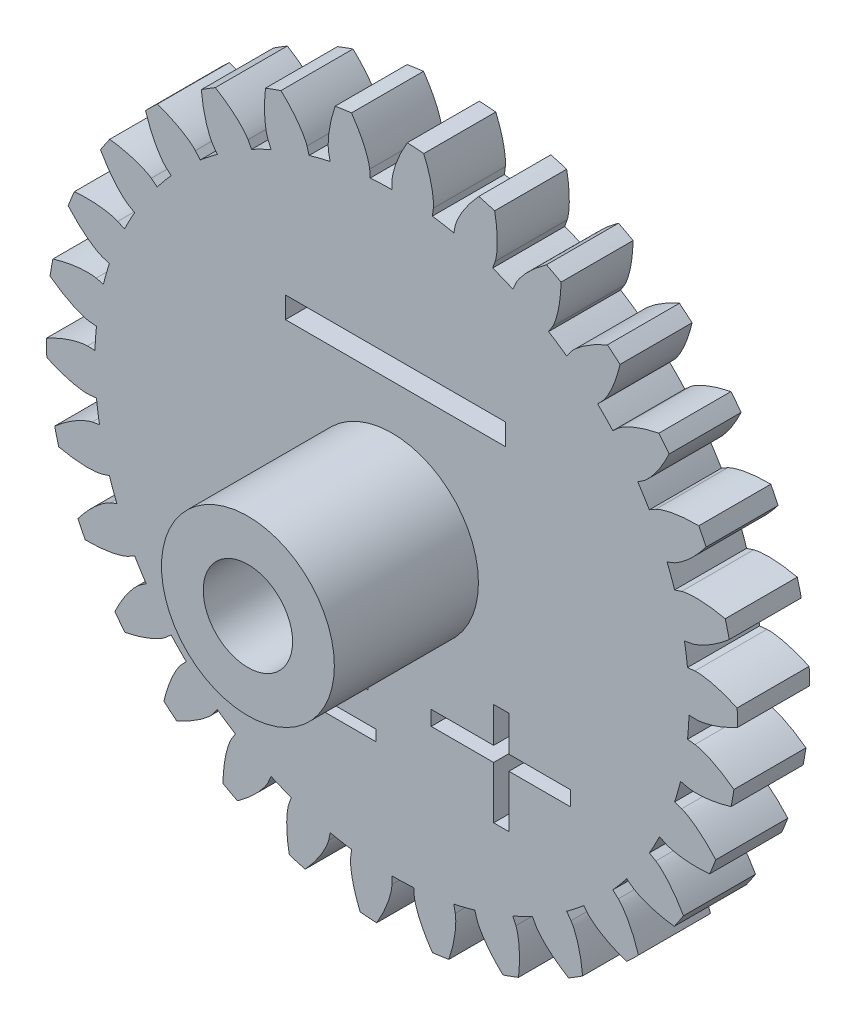
SolidWorks part; units mm, degrees
ref_plane "前视基准面" through (0, 0, 0) normal (0, 0, 1) x (1, 0, 0)
ref_plane "上视基准面" through (0, 0, 0) normal (0, 1, 0) x (1, 0, 0)
ref_plane "右视基准面" through (0, 0, 0) normal (1, 0, 0) x (0, 0, -1)
sketch "草图1" plane through (0, 0, 0) normal (0, 0, 1) x (1, 0, 0)
  line L0 (0, 0) -> (0.3541, 22.4972) construction
  line L1 (0, 0) -> (2.0291, 29.7506) construction
  line L2 (0, 0) -> (5.2133, 29.8652) construction
  circle A0 centre (0, 0) radius 22.5
  circle A1 centre (0, 0) radius 24
  circle A2 centre (0, 0) radius 20.625
  spline S0 degree 4 poles (0, 21.1431) (0.0004, 21.1602) (0.0026, 21.2083) (0.0115, 21.2988) (0.0325, 21.446) (0.069, 21.6322) (0.127, 21.8709) (0.2093, 22.149) (0.3142, 22.451) (0.4437, 22.7748) (0.5865, 23.0933) (0.7411, 23.4062) (0.9065, 23.7136) (1.1191, 24.0799) (1.3926, 24.5114) (1.7356, 25.0015) (2.1566, 25.5426) (2.6112, 26.0723) (3.0895, 26.5812) (3.5886, 27.069) (4.1076, 27.5366) (4.6431, 27.9833) (5.1275, 28.3576) (5.5491, 28.6644) (5.9109, 28.9144) (6.1952, 29.1048) (6.5001, 29.3003) (6.7749, 29.4718) (7.175, 29.7103) (7.4719, 29.8798) (7.9311, 30.1336) (8.0994, 30.2164) (8.2684, 30.3055) knots 0 0 0 0 0 0.005377 0.015084 0.028532 0.04661 0.064855 0.092111 0.119476 0.146842 0.174209 0.201575 0.228941 0.256307 0.307035 0.361767 0.4165 0.471232 0.525964 0.580697 0.635429 0.690161 0.744894 0.77226 0.799626 0.826992 0.854358 0.881725 0.909091 0.954545 1 1 1 1 1 construction
  spline S1 degree 4 poles (0, 21.1431) (0.0004, 21.1602) (0.0026, 21.2083) (0.0115, 21.2988) (0.0325, 21.446) (0.069, 21.6322) (0.127, 21.8709) (0.2093, 22.149) (0.3142, 22.451) (0.4437, 22.7748) (0.5865, 23.0933) (0.7411, 23.4062) (0.8806, 23.6655) (0.9833, 23.8453) (1.0443, 23.9485) (1.0609, 23.9765) knots 0 0 0 0 0 0.005377 0.015084 0.028532 0.04661 0.064855 0.092111 0.119476 0.146842 0.174209 0.201575 0.228941 0.239168 0.239168 0.239168 0.239168 0.239168
  spline S2 degree 2 poles (0, 21.1431) (0, 20.884) (0, 20.625) knots 0 0 0 1 1 1
  spline S3 degree 2 poles (2.8708, 20.9473) (2.8356, 20.6906) (2.8004, 20.434) knots 0 0 0 1 1 1
  spline S4 degree 4 poles (2.8708, 20.9473) (2.8727, 20.9643) (2.877, 21.0122) (2.8805, 21.1032) (2.8796, 21.2518) (2.8688, 21.4412) (2.8438, 21.6856) (2.8, 21.9723) (2.737, 22.2857) (2.6527, 22.6241) (2.5545, 22.9591) (2.4438, 23.2901) (2.3408, 23.5659) (2.2634, 23.758) (2.2171, 23.8685) (2.2044, 23.8986) knots 0 0 0 0 0 0.005377 0.015084 0.028532 0.04661 0.064855 0.092111 0.119476 0.146842 0.174209 0.201575 0.228941 0.239168 0.239168 0.239168 0.239168 0.239168
  spline S5 degree 2 poles (4.3959, 20.6811) (4.342, 20.4277) (4.2882, 20.1743) knots 0 0 0 1 1 1
  spline S6 degree 4 poles (4.3959, 20.6811) (4.3998, 20.6977) (4.412, 20.7443) (4.4395, 20.831) (4.4907, 20.9706) (4.565, 21.1451) (4.6714, 21.3665) (4.8097, 21.6215) (4.9752, 21.895) (5.1692, 22.1848) (5.3751, 22.4667) (5.5914, 22.7406) (5.7817, 22.9653) (5.9196, 23.1198) (6.0006, 23.2081) (6.0228, 23.232) knots 0 0 0 0 0 0.005377 0.015084 0.028532 0.04661 0.064855 0.092111 0.119476 0.146842 0.174209 0.201575 0.228941 0.239168 0.239168 0.239168 0.239168 0.239168
  dimension "D1" = 45
  dimension "D2" = 48
  dimension "D3" = 41.25
  dimension "D4" = 3
  dimension "D5" = 9
sketch "草图2" plane through (0, 0, 0) normal (0, 0, 1) x (1, 0, 0)
  circle A0 centre (0, 0) radius 24 construction
  circle A1 centre (0, 0) radius 20.625 construction
  arc A2 (2.2044, 23.8986) -> (1.0609, 23.9765) centre (0, 0) ccw
  arc A3 (4.2882, 20.1743) -> (2.8004, 20.434) centre (0, 0) ccw
  arc A4 (7.125, 22.918) -> (6.0228, 23.232) centre (0, 0) ccw
  arc A5 (8.3889, 18.8419) -> (6.9877, 19.4052) centre (0, 0) ccw
  arc A6 (11.7342, 20.9358) -> (10.7214, 21.4721) centre (0, 0) ccw
  arc A7 (12.1231, 16.686) -> (10.8696, 17.5284) centre (0, 0) ccw
  arc A8 (15.8306, 18.0386) -> (14.9514, 18.7738) centre (0, 0) ccw
  arc A9 (15.3274, 13.8008) -> (14.2764, 14.8854) centre (0, 0) ccw
  arc A10 (19.2351, 14.3531) -> (18.528, 15.255) centre (0, 0) ccw
  arc A11 (17.8618, 10.3125) -> (17.0593, 11.5919) centre (0, 0) ccw
  arc A12 (21.7989, 10.0402) -> (21.2948, 11.0695) centre (0, 0) ccw
  arc A13 (19.6155, 6.3735) -> (19.0966, 7.7918) centre (0, 0) ccw
  arc A14 (23.4101, 5.2886) -> (23.1309, 6.4001) centre (0, 0) ccw
  arc A15 (20.512, 2.1559) -> (20.2993, 3.6511) centre (0, 0) ccw
  arc A16 (23.9981, 0.3058) -> (23.9561, 1.4511) centre (0, 0) ccw
  arc A17 (20.512, -2.1559) -> (20.6148, -0.6491) centre (0, 0) ccw
  arc A18 (23.5372, -4.6904) -> (23.7343, -3.5614) centre (0, 0) ccw
  arc A19 (19.6155, -6.3735) -> (20.0293, -4.921) centre (0, 0) ccw
  arc A20 (22.0477, -9.4815) -> (22.4752, -8.4182) centre (0, 0) ccw
  arc A21 (17.8618, -10.3125) -> (18.5685, -8.9778) centre (0, 0) ccw
  arc A22 (19.5946, -13.8583) -> (20.2338, -12.9071) centre (0, 0) ccw
  arc A23 (15.3274, -13.8008) -> (16.2962, -12.6422) centre (0, 0) ccw
  arc A24 (16.2851, -17.6294) -> (17.1081, -16.8319) centre (0, 0) ccw
  arc A25 (12.1231, -16.686) -> (13.3116, -15.7541) centre (0, 0) ccw
  arc A26 (12.2639, -20.63) -> (13.2347, -20.021) centre (0, 0) ccw
  arc A27 (8.3889, -18.8419) -> (9.7452, -18.1775) centre (0, 0) ccw
  arc A28 (7.7066, -22.729) -> (8.7829, -22.3352) centre (0, 0) ccw
  arc A29 (4.2882, -20.1743) -> (5.753, -19.8064) centre (0, 0) ccw
  arc A30 (2.8126, -23.8346) -> (3.9472, -23.6732) centre (0, 0) ccw
  arc A31 (0, -20.625) -> (1.5092, -20.5697) centre (0, 0) ccw
  arc A32 (-2.2044, -23.8986) -> (-1.0609, -23.9765) centre (0, 0) ccw
  arc A33 (-4.2882, -20.1743) -> (-2.8004, -20.434) centre (0, 0) ccw
  arc A34 (-7.125, -22.918) -> (-6.0228, -23.232) centre (0, 0) ccw
  arc A35 (-8.3889, -18.8419) -> (-6.9877, -19.4052) centre (0, 0) ccw
  arc A36 (-11.7342, -20.9358) -> (-10.7214, -21.4721) centre (0, 0) ccw
  arc A37 (-12.1231, -16.686) -> (-10.8696, -17.5284) centre (0, 0) ccw
  arc A38 (-15.8306, -18.0386) -> (-14.9514, -18.7738) centre (0, 0) ccw
  arc A39 (-15.3274, -13.8008) -> (-14.2764, -14.8854) centre (0, 0) ccw
  arc A40 (-19.2351, -14.3531) -> (-18.528, -15.255) centre (0, 0) ccw
  arc A41 (-17.8618, -10.3125) -> (-17.0593, -11.5919) centre (0, 0) ccw
  arc A42 (-21.7989, -10.0402) -> (-21.2948, -11.0695) centre (0, 0) ccw
  arc A43 (-19.6155, -6.3735) -> (-19.0966, -7.7918) centre (0, 0) ccw
  arc A44 (-23.4101, -5.2886) -> (-23.1309, -6.4001) centre (0, 0) ccw
  arc A45 (-20.512, -2.1559) -> (-20.2993, -3.6511) centre (0, 0) ccw
  arc A46 (-23.9981, -0.3058) -> (-23.9561, -1.4511) centre (0, 0) ccw
  arc A47 (-20.512, 2.1559) -> (-20.6148, 0.6491) centre (0, 0) ccw
  arc A48 (-23.5372, 4.6904) -> (-23.7343, 3.5614) centre (0, 0) ccw
  arc A49 (-19.6155, 6.3735) -> (-20.0293, 4.921) centre (0, 0) ccw
  arc A50 (-22.0477, 9.4815) -> (-22.4752, 8.4182) centre (0, 0) ccw
  arc A51 (-17.8618, 10.3125) -> (-18.5685, 8.9778) centre (0, 0) ccw
  arc A52 (-19.5946, 13.8583) -> (-20.2338, 12.9071) centre (0, 0) ccw
  arc A53 (-15.3274, 13.8008) -> (-16.2962, 12.6422) centre (0, 0) ccw
  arc A54 (-16.2851, 17.6294) -> (-17.1081, 16.8319) centre (0, 0) ccw
  arc A55 (-12.1231, 16.686) -> (-13.3116, 15.7541) centre (0, 0) ccw
  arc A56 (-12.2639, 20.63) -> (-13.2347, 20.021) centre (0, 0) ccw
  arc A57 (-8.3889, 18.8419) -> (-9.7452, 18.1775) centre (0, 0) ccw
  arc A58 (-7.7066, 22.729) -> (-8.7829, 22.3352) centre (0, 0) ccw
  arc A59 (-4.2882, 20.1743) -> (-5.753, 19.8064) centre (0, 0) ccw
  arc A60 (-2.8126, 23.8346) -> (-3.9472, 23.6732) centre (0, 0) ccw
  arc A61 (0, 20.625) -> (-1.5092, 20.5697) centre (0, 0) ccw
  spline S2 degree 2 poles (274.4242, 2002.4129) (2.8348, 20.6849) (-268.7546, -1961.043) knots -3860.352679 -3860.352679 -3860.352679 3861.374869 3861.374869 3861.374869 only from (2.8708, 20.9473) to (2.8004, 20.434) construction
  spline S3 degree 4 poles (-1979.2072, 287.1741) (-31.6416, 21.293) (1.8963, 18.3394) (2.8884, 19.7632) (2.8796, 21.2518) (2.8688, 21.4412) (2.8438, 21.6856) (2.8, 21.9723) (2.737, 22.2857) (2.6527, 22.6241) (2.5545, 22.9591) (2.4438, 23.2901) (-2.8505, 37.472) (-34.1394, 41.319) (58.2669, 25.3379) (-1676.5067, -1063.1461) knots -0.420205 -0.420205 -0.420205 -0.420205 -0.420205 0.005377 0.015084 0.028532 0.04661 0.064855 0.092111 0.119476 0.146842 0.174209 0.201575 0.228941 4.89418 4.89418 4.89418 4.89418 4.89418 only from (2.8708, 20.9473) to (2.2044, 23.8986) construction
  spline S4 degree 2 poles (0, 2021.1299) (0, 20.8783) (0, -1979.3733) knots -3860.352679 -3860.352679 -3860.352679 3861.374869 3861.374869 3861.374869 only from (0, 21.1431) to (0, 20.625) construction
  spline S5 degree 4 poles (1999.8702, 15.7826) (34.2397, 16.7996) (0.6114, 18.4271) (-0.1783, 19.9724) (0.0325, 21.446) (0.069, 21.6322) (0.127, 21.8709) (0.2093, 22.149) (0.3142, 22.451) (0.4437, 22.7748) (0.5865, 23.0933) (0.7411, 23.4062) (7.912, 36.7379) (39.4334, 36.301) (-54.287, 33.0146) (1516.6297, -1280.9329) knots -0.420205 -0.420205 -0.420205 -0.420205 -0.420205 0.005377 0.015084 0.028532 0.04661 0.064855 0.092111 0.119476 0.146842 0.174209 0.201575 0.228941 4.89418 4.89418 4.89418 4.89418 4.89418 only from (0, 21.1431) to (1.0609, 23.9765) construction
  spline S6 degree 4 poles (4.3959, 20.6811) (4.3998, 20.6977) (4.412, 20.7443) (4.4395, 20.831) (4.4907, 20.9706) (4.565, 21.1451) (4.6714, 21.3665) (4.8097, 21.6215) (4.9752, 21.895) (5.1692, 22.1848) (5.3751, 22.4667) (5.5914, 22.7406) (5.7817, 22.9653) (5.9196, 23.1198) (6.0006, 23.2081) (6.0228, 23.232) knots 0 0 0 0 0 0.005377 0.015084 0.028532 0.04661 0.064855 0.092111 0.119476 0.146842 0.174209 0.201575 0.228941 0.239168 0.239168 0.239168 0.239168 0.239168
  spline S7 degree 2 poles (4.3959, 20.6811) (4.342, 20.4277) (4.2882, 20.1743) knots 0 0 0 1 1 1
  spline S8 degree 2 poles (2.8708, 20.9473) (2.8356, 20.6906) (2.8004, 20.434) knots 0 0 0 1 1 1
  spline S9 degree 4 poles (2.8708, 20.9473) (2.8727, 20.9643) (2.877, 21.0122) (2.8805, 21.1032) (2.8796, 21.2518) (2.8688, 21.4412) (2.8438, 21.6856) (2.8, 21.9723) (2.737, 22.2857) (2.6527, 22.6241) (2.5545, 22.9591) (2.4438, 23.2901) (2.3408, 23.5659) (2.2634, 23.758) (2.2171, 23.8685) (2.2044, 23.8986) knots 0 0 0 0 0 0.005377 0.015084 0.028532 0.04661 0.064855 0.092111 0.119476 0.146842 0.174209 0.201575 0.228941 0.239168 0.239168 0.239168 0.239168 0.239168
  spline S10 degree 2 poles (0, 21.1431) (0, 20.884) (0, 20.625) knots 0 0 0 1 1 1
  spline S11 degree 4 poles (0, 21.1431) (0.0004, 21.1602) (0.0026, 21.2083) (0.0115, 21.2988) (0.0325, 21.446) (0.069, 21.6322) (0.127, 21.8709) (0.2093, 22.149) (0.3142, 22.451) (0.4437, 22.7748) (0.5865, 23.0933) (0.7411, 23.4062) (0.8806, 23.6655) (0.9833, 23.8453) (1.0443, 23.9485) (1.0609, 23.9765) knots 0 0 0 0 0 0.005377 0.015084 0.028532 0.04661 0.064855 0.092111 0.119476 0.146842 0.174209 0.201575 0.228941 0.239168 0.239168 0.239168 0.239168 0.239168
  spline S12 degree 4 poles (7.1632, 19.8927) (7.1687, 19.9089) (7.1828, 19.9549) (7.2052, 20.0431) (7.2352, 20.1887) (7.264, 20.3762) (7.2903, 20.6204) (7.3071, 20.91) (7.3107, 21.2297) (7.2985, 21.5782) (7.2721, 21.9262) (7.2326, 22.2731) (7.1893, 22.5642) (7.1535, 22.7682) (7.1312, 22.886) (7.125, 22.918) knots 0 0 0 0 0 0.005377 0.015084 0.028532 0.04661 0.064855 0.092111 0.119476 0.146842 0.174209 0.201575 0.228941 0.239168 0.239168 0.239168 0.239168 0.239168
  spline S13 degree 2 poles (7.1632, 19.8927) (7.0754, 19.649) (6.9877, 19.4052) knots 0 0 0 1 1 1
  spline S14 degree 4 poles (8.5997, 19.3152) (8.607, 19.3307) (8.6286, 19.3736) (8.6735, 19.4528) (8.7526, 19.5786) (8.8616, 19.7339) (9.0117, 19.9284) (9.2, 20.149) (9.4187, 20.3822) (9.6687, 20.6253) (9.9287, 20.8582) (10.1972, 21.0812) (10.4301, 21.2613) (10.5971, 21.3838) (10.6947, 21.4533) (10.7214, 21.4721) knots 0 0 0 0 0 0.005377 0.015084 0.028532 0.04661 0.064855 0.092111 0.119476 0.146842 0.174209 0.201575 0.228941 0.239168 0.239168 0.239168 0.239168 0.239168
  spline S15 degree 2 poles (8.5997, 19.3152) (8.4943, 19.0785) (8.3889, 18.8419) knots 0 0 0 1 1 1
  spline S16 degree 4 poles (11.1426, 17.9687) (11.1513, 17.9834) (11.1747, 18.0254) (11.2149, 18.1071) (11.2746, 18.2432) (11.3417, 18.4207) (11.4182, 18.6541) (11.4949, 18.9338) (11.5648, 19.2458) (11.6254, 19.5892) (11.6719, 19.9352) (11.7054, 20.2826) (11.7235, 20.5764) (11.731, 20.7834) (11.7336, 20.9032) (11.7342, 20.9358) knots 0 0 0 0 0 0.005377 0.015084 0.028532 0.04661 0.064855 0.092111 0.119476 0.146842 0.174209 0.201575 0.228941 0.239168 0.239168 0.239168 0.239168 0.239168
  spline S17 degree 2 poles (11.1426, 17.9687) (11.0061, 17.7485) (10.8696, 17.5284) knots 0 0 0 1 1 1
  spline S18 degree 4 poles (12.4276, 17.1051) (12.438, 17.1188) (12.468, 17.1563) (12.5284, 17.2244) (12.632, 17.331) (12.7709, 17.4603) (12.9581, 17.6193) (13.1882, 17.7959) (13.4505, 17.9785) (13.7456, 18.1644) (14.0484, 18.3381) (14.3574, 18.5004) (14.6226, 18.6282) (14.8115, 18.7133) (14.9214, 18.761) (14.9514, 18.7738) knots 0 0 0 0 0 0.005377 0.015084 0.028532 0.04661 0.064855 0.092111 0.119476 0.146842 0.174209 0.201575 0.228941 0.239168 0.239168 0.239168 0.239168 0.239168
  spline S19 degree 2 poles (12.4276, 17.1051) (12.2753, 16.8955) (12.1231, 16.686) knots 0 0 0 1 1 1
  spline S20 degree 4 poles (14.635, 15.2593) (14.6466, 15.272) (14.6782, 15.3082) (14.7345, 15.3797) (14.8212, 15.5005) (14.9238, 15.66) (15.0471, 15.8725) (15.1803, 16.1302) (15.3135, 16.4207) (15.4442, 16.7441) (15.5616, 17.0728) (15.6666, 17.4057) (15.7454, 17.6893) (15.7958, 17.8902) (15.8232, 18.0069) (15.8306, 18.0386) knots 0 0 0 0 0 0.005377 0.015084 0.028532 0.04661 0.064855 0.092111 0.119476 0.146842 0.174209 0.201575 0.228941 0.239168 0.239168 0.239168 0.239168 0.239168
  spline S21 degree 2 poles (14.635, 15.2593) (14.4557, 15.0724) (14.2764, 14.8854) knots 0 0 0 1 1 1
  spline S22 degree 4 poles (15.7124, 14.1475) (15.7254, 14.1587) (15.7626, 14.1891) (15.8358, 14.2432) (15.9592, 14.326) (16.122, 14.4235) (16.3382, 14.5401) (16.5999, 14.6651) (16.8946, 14.7891) (17.2219, 14.9095) (17.5541, 15.0165) (17.8901, 15.111) (18.1761, 15.1809) (18.3785, 15.2249) (18.496, 15.2487) (18.528, 15.255) knots 0 0 0 0 0 0.005377 0.015084 0.028532 0.04661 0.064855 0.092111 0.119476 0.146842 0.174209 0.201575 0.228941 0.239168 0.239168 0.239168 0.239168 0.239168
  spline S23 degree 2 poles (15.7124, 14.1475) (15.5199, 13.9742) (15.3274, 13.8008) knots 0 0 0 1 1 1
  spline S24 degree 4 poles (17.4878, 11.8831) (17.5017, 11.893) (17.5402, 11.9219) (17.6102, 11.9801) (17.72, 12.0802) (17.8536, 12.215) (18.0184, 12.3971) (18.2022, 12.6215) (18.3929, 12.878) (18.588, 13.1671) (18.7712, 13.4643) (18.9431, 13.768) (19.0792, 14.0291) (19.1702, 14.2152) (19.2213, 14.3236) (19.2351, 14.3531) knots 0 0 0 0 0 0.005377 0.015084 0.028532 0.04661 0.064855 0.092111 0.119476 0.146842 0.174209 0.201575 0.228941 0.239168 0.239168 0.239168 0.239168 0.239168
  spline S25 degree 2 poles (17.4878, 11.8831) (17.2735, 11.7375) (17.0593, 11.5919) knots 0 0 0 1 1 1
  spline S26 degree 4 poles (18.3104, 10.5715) (18.3255, 10.5798) (18.3682, 10.6019) (18.4511, 10.6395) (18.589, 10.6948) (18.7685, 10.7564) (19.0042, 10.8255) (19.2862, 10.8933) (19.6002, 10.9534) (19.9454, 11.0031) (20.2926, 11.0387) (20.641, 11.0613) (20.9352, 11.0701) (21.1423, 11.0711) (21.2622, 11.0699) (21.2948, 11.0695) knots 0 0 0 0 0 0.005377 0.015084 0.028532 0.04661 0.064855 0.092111 0.119476 0.146842 0.174209 0.201575 0.228941 0.239168 0.239168 0.239168 0.239168 0.239168
  spline S27 degree 2 poles (18.3104, 10.5715) (18.0861, 10.442) (17.8618, 10.3125) knots 0 0 0 1 1 1
  spline S28 degree 4 poles (19.5763, 7.9875) (19.592, 7.9943) (19.6356, 8.0145) (19.7161, 8.057) (19.8444, 8.1321) (20.0031, 8.2361) (20.2021, 8.38) (20.4286, 8.5613) (20.6685, 8.7725) (20.9194, 9.0148) (21.1604, 9.2673) (21.3917, 9.5287) (21.5791, 9.7558) (21.7068, 9.9188) (21.7793, 10.0142) (21.7989, 10.0402) knots 0 0 0 0 0 0.005377 0.015084 0.028532 0.04661 0.064855 0.092111 0.119476 0.146842 0.174209 0.201575 0.228941 0.239168 0.239168 0.239168 0.239168 0.239168
  spline S29 degree 2 poles (19.5763, 7.9875) (19.3364, 7.8896) (19.0966, 7.7918) knots 0 0 0 1 1 1
  spline S30 degree 4 poles (20.1083, 6.5336) (20.1247, 6.5385) (20.1711, 6.5512) (20.26, 6.5708) (20.4064, 6.5962) (20.5947, 6.6191) (20.8397, 6.6377) (21.1296, 6.6454) (21.4492, 6.6389) (21.7972, 6.6158) (22.1443, 6.5784) (22.4897, 6.5281) (22.7793, 6.4755) (22.9821, 6.4334) (23.0991, 6.4073) (23.1309, 6.4001) knots 0 0 0 0 0 0.005377 0.015084 0.028532 0.04661 0.064855 0.092111 0.119476 0.146842 0.174209 0.201575 0.228941 0.239168 0.239168 0.239168 0.239168 0.239168
  spline S31 degree 2 poles (20.1083, 6.5336) (19.8619, 6.4535) (19.6155, 6.3735) knots 0 0 0 1 1 1
  spline S32 degree 4 poles (20.8092, 3.7428) (20.826, 3.7462) (20.8728, 3.7569) (20.9604, 3.7817) (21.1015, 3.8285) (21.2783, 3.8973) (21.503, 3.9966) (21.7622, 4.1268) (22.0408, 4.2836) (22.3365, 4.4684) (22.6247, 4.6653) (22.9054, 4.8729) (23.1359, 5.056) (23.2947, 5.189) (23.3854, 5.2672) (23.4101, 5.2886) knots 0 0 0 0 0 0.005377 0.015084 0.028532 0.04661 0.064855 0.092111 0.119476 0.146842 0.174209 0.201575 0.228941 0.239168 0.239168 0.239168 0.239168 0.239168
  spline S33 degree 2 poles (20.8092, 3.7428) (20.5542, 3.697) (20.2993, 3.6511) knots 0 0 0 1 1 1
  spline S34 degree 4 poles (21.0273, 2.2101) (21.0443, 2.2115) (21.0924, 2.2143) (21.1834, 2.2149) (21.3319, 2.2093) (21.5209, 2.1926) (21.7643, 2.1598) (22.0495, 2.1071) (22.3608, 2.0343) (22.6964, 1.9393) (23.0281, 1.8306) (23.3555, 1.7095) (23.6279, 1.5979) (23.8175, 1.5146) (23.9265, 1.4648) (23.9561, 1.4511) knots 0 0 0 0 0 0.005377 0.015084 0.028532 0.04661 0.064855 0.092111 0.119476 0.146842 0.174209 0.201575 0.228941 0.239168 0.239168 0.239168 0.239168 0.239168
  spline S35 degree 2 poles (21.0273, 2.2101) (20.7696, 2.183) (20.512, 2.1559) knots 0 0 0 1 1 1
  spline S36 degree 4 poles (21.1326, -0.6654) (21.1498, -0.6656) (21.1978, -0.6649) (21.2887, -0.6589) (21.4364, -0.6424) (21.6236, -0.6119) (21.864, -0.5614) (22.1446, -0.4879) (22.4497, -0.3926) (22.7774, -0.2733) (23.1003, -0.1406) (23.418, 0.0041) (23.6815, 0.1353) (23.8645, 0.2324) (23.9695, 0.29) (23.9981, 0.3058) knots 0 0 0 0 0 0.005377 0.015084 0.028532 0.04661 0.064855 0.092111 0.119476 0.146842 0.174209 0.201575 0.228941 0.239168 0.239168 0.239168 0.239168 0.239168
  spline S37 degree 2 poles (21.1326, -0.6654) (20.8737, -0.6573) (20.6148, -0.6491) knots 0 0 0 1 1 1
  spline S38 degree 4 poles (21.0273, -2.2101) (21.0443, -2.2122) (21.0918, -2.2195) (21.181, -2.2378) (21.3251, -2.2741) (21.5065, -2.3298) (21.7378, -2.4124) (22.0058, -2.5233) (22.2951, -2.6593) (22.6036, -2.8219) (22.9055, -2.9972) (23.2005, -3.1837) (23.4438, -3.3495) (23.6119, -3.4705) (23.7082, -3.5418) (23.7343, -3.5614) knots 0 0 0 0 0 0.005377 0.015084 0.028532 0.04661 0.064855 0.092111 0.119476 0.146842 0.174209 0.201575 0.228941 0.239168 0.239168 0.239168 0.239168 0.239168
  spline S39 degree 2 poles (21.0273, -2.2101) (20.7696, -2.183) (20.512, -2.1559) knots 0 0 0 1 1 1
  spline S40 degree 4 poles (20.5325, -5.0446) (20.5492, -5.0483) (20.5964, -5.0576) (20.6865, -5.0706) (20.8344, -5.0853) (21.0239, -5.0943) (21.2695, -5.095) (21.5593, -5.0814) (21.8775, -5.0515) (22.2229, -5.003) (22.5663, -4.9403) (22.9071, -4.8649) (23.1921, -4.7913) (23.3913, -4.7344) (23.506, -4.6999) (23.5372, -4.6904) knots 0 0 0 0 0 0.005377 0.015084 0.028532 0.04661 0.064855 0.092111 0.119476 0.146842 0.174209 0.201575 0.228941 0.239168 0.239168 0.239168 0.239168 0.239168
  spline S41 degree 2 poles (20.5325, -5.0446) (20.2809, -4.9828) (20.0293, -4.921) knots 0 0 0 1 1 1
  spline S42 degree 4 poles (20.1083, -6.5336) (20.1245, -6.5392) (20.1694, -6.5562) (20.2529, -6.5926) (20.3863, -6.6581) (20.5521, -6.7503) (20.7612, -6.8792) (21.0003, -7.0434) (21.255, -7.2366) (21.523, -7.4598) (21.7818, -7.694) (22.0316, -7.9378) (22.2351, -8.1505) (22.3744, -8.3038) (22.4537, -8.3937) (22.4752, -8.4182) knots 0 0 0 0 0 0.005377 0.015084 0.028532 0.04661 0.064855 0.092111 0.119476 0.146842 0.174209 0.201575 0.228941 0.239168 0.239168 0.239168 0.239168 0.239168
  spline S43 degree 2 poles (20.1083, -6.5336) (19.8619, -6.4535) (19.6155, -6.3735) knots 0 0 0 1 1 1
  spline S44 degree 4 poles (19.0349, -9.2033) (19.0505, -9.2104) (19.0948, -9.2293) (19.1802, -9.2608) (19.3218, -9.3059) (19.5053, -9.3541) (19.7454, -9.4058) (20.0317, -9.4528) (20.3492, -9.4897) (20.6971, -9.5141) (21.046, -9.5242) (21.395, -9.5212) (21.6892, -9.5085) (21.8958, -9.4943) (22.0152, -9.4844) (22.0477, -9.4815) knots 0 0 0 0 0 0.005377 0.015084 0.028532 0.04661 0.064855 0.092111 0.119476 0.146842 0.174209 0.201575 0.228941 0.239168 0.239168 0.239168 0.239168 0.239168
  spline S45 degree 2 poles (19.0349, -9.2033) (18.8017, -9.0906) (18.5685, -8.9778) knots 0 0 0 1 1 1
  spline S46 degree 4 poles (18.3104, -10.5715) (18.3251, -10.5804) (18.3656, -10.6064) (18.4396, -10.6594) (18.5565, -10.7512) (18.6995, -10.8758) (18.8772, -11.0454) (19.077, -11.2557) (19.286, -11.4976) (19.5017, -11.7717) (19.7061, -12.0546) (19.8998, -12.345) (20.0546, -12.5954) (20.159, -12.7743) (20.2179, -12.8786) (20.2338, -12.9071) knots 0 0 0 0 0 0.005377 0.015084 0.028532 0.04661 0.064855 0.092111 0.119476 0.146842 0.174209 0.201575 0.228941 0.239168 0.239168 0.239168 0.239168 0.239168
  spline S47 degree 2 poles (18.3104, -10.5715) (18.0861, -10.442) (17.8618, -10.3125) knots 0 0 0 1 1 1
  spline S48 degree 4 poles (16.7055, -12.9598) (16.7193, -12.97) (16.7586, -12.9977) (16.8356, -13.0462) (16.9648, -13.1197) (17.1342, -13.2051) (17.3584, -13.3056) (17.6286, -13.411) (17.9315, -13.5132) (18.2667, -13.6093) (18.6059, -13.6918) (18.9479, -13.7614) (19.2383, -13.8101) (19.4433, -13.8392) (19.5622, -13.8543) (19.5946, -13.8583) knots 0 0 0 0 0 0.005377 0.015084 0.028532 0.04661 0.064855 0.092111 0.119476 0.146842 0.174209 0.201575 0.228941 0.239168 0.239168 0.239168 0.239168 0.239168
  spline S49 degree 2 poles (16.7055, -12.9598) (16.5008, -12.801) (16.2962, -12.6422) knots 0 0 0 1 1 1
  spline S50 degree 4 poles (15.7124, -14.1475) (15.7249, -14.1592) (15.7591, -14.193) (15.8204, -14.2603) (15.9157, -14.3743) (16.0297, -14.526) (16.1683, -14.7288) (16.3199, -14.9761) (16.4741, -15.2561) (16.628, -15.569) (16.7692, -15.8883) (16.8983, -16.2126) (16.9977, -16.4897) (17.0625, -16.6864) (17.0985, -16.8007) (17.1081, -16.8319) knots 0 0 0 0 0 0.005377 0.015084 0.028532 0.04661 0.064855 0.092111 0.119476 0.146842 0.174209 0.201575 0.228941 0.239168 0.239168 0.239168 0.239168 0.239168
  spline S51 degree 2 poles (15.7124, -14.1475) (15.5199, -13.9742) (15.3274, -13.8008) knots 0 0 0 1 1 1
  spline S52 degree 4 poles (13.646, -16.1499) (13.6573, -16.1627) (13.69, -16.198) (13.7553, -16.2614) (13.8663, -16.3602) (14.0143, -16.4789) (14.2127, -16.6238) (14.455, -16.7832) (14.7301, -16.9461) (15.038, -17.1098) (15.3526, -17.2609) (15.6727, -17.4002) (15.9466, -17.5082) (16.1411, -17.5793) (16.2543, -17.6188) (16.2851, -17.6294) knots 0 0 0 0 0 0.005377 0.015084 0.028532 0.04661 0.064855 0.092111 0.119476 0.146842 0.174209 0.201575 0.228941 0.239168 0.239168 0.239168 0.239168 0.239168
  spline S53 degree 2 poles (13.646, -16.1499) (13.4788, -15.952) (13.3116, -15.7541) knots 0 0 0 1 1 1
  spline S54 degree 4 poles (12.4276, -17.1051) (12.4374, -17.1192) (12.4638, -17.1594) (12.5098, -17.2379) (12.5793, -17.3693) (12.6593, -17.5413) (12.7526, -17.7685) (12.8496, -18.0419) (12.9421, -18.3479) (13.0277, -18.686) (13.0994, -19.0276) (13.1582, -19.3717) (13.1978, -19.6634) (13.2204, -19.8693) (13.2318, -19.9886) (13.2347, -20.021) knots 0 0 0 0 0 0.005377 0.015084 0.028532 0.04661 0.064855 0.092111 0.119476 0.146842 0.174209 0.201575 0.228941 0.239168 0.239168 0.239168 0.239168 0.239168
  spline S55 degree 2 poles (12.4276, -17.1051) (12.2753, -16.8955) (12.1231, -16.686) knots 0 0 0 1 1 1
  spline S56 degree 4 poles (9.99, -18.6341) (9.9984, -18.649) (10.0231, -18.6903) (10.0737, -18.7659) (10.1618, -18.8857) (10.2819, -19.0326) (10.4458, -19.2155) (10.6497, -19.4218) (10.8849, -19.6383) (11.152, -19.8625) (11.4284, -20.0757) (11.7125, -20.2785) (11.9579, -20.4411) (12.1335, -20.551) (12.2359, -20.6132) (12.2639, -20.63) knots 0 0 0 0 0 0.005377 0.015084 0.028532 0.04661 0.064855 0.092111 0.119476 0.146842 0.174209 0.201575 0.228941 0.239168 0.239168 0.239168 0.239168 0.239168
  spline S57 degree 2 poles (9.99, -18.6341) (9.8676, -18.4058) (9.7452, -18.1775) knots 0 0 0 1 1 1
  spline S58 degree 4 poles (8.5997, -19.3152) (8.6063, -19.331) (8.6238, -19.3758) (8.6525, -19.4621) (8.6931, -19.6051) (8.7356, -19.79) (8.7797, -20.0317) (8.8176, -20.3192) (8.8446, -20.6378) (8.858, -20.9863) (8.8571, -21.3353) (8.8431, -21.6841) (8.8212, -21.9777) (8.8004, -22.1837) (8.7868, -22.3028) (8.7829, -22.3352) knots 0 0 0 0 0 0.005377 0.015084 0.028532 0.04661 0.064855 0.092111 0.119476 0.146842 0.174209 0.201575 0.228941 0.239168 0.239168 0.239168 0.239168 0.239168
  spline S59 degree 2 poles (8.5997, -19.3152) (8.4943, -19.0785) (8.3889, -18.8419) knots 0 0 0 1 1 1
  spline S60 degree 4 poles (5.8975, -20.3039) (5.9026, -20.3203) (5.9182, -20.3658) (5.9519, -20.4503) (6.0132, -20.5857) (6.1001, -20.7544) (6.2224, -20.9674) (6.379, -21.2116) (6.564, -21.4723) (6.7787, -21.7471) (7.0047, -22.0131) (7.2404, -22.2705) (7.4467, -22.4806) (7.5955, -22.6246) (7.6828, -22.7068) (7.7066, -22.729) knots 0 0 0 0 0 0.005377 0.015084 0.028532 0.04661 0.064855 0.092111 0.119476 0.146842 0.174209 0.201575 0.228941 0.239168 0.239168 0.239168 0.239168 0.239168
  spline S61 degree 2 poles (5.8975, -20.3039) (5.8252, -20.0552) (5.753, -19.8064) knots 0 0 0 1 1 1
  spline S62 degree 4 poles (4.3959, -20.6811) (4.3991, -20.6979) (4.4069, -20.7454) (4.417, -20.8358) (4.427, -20.9841) (4.4301, -21.1738) (4.423, -21.4193) (4.4003, -21.7085) (4.3605, -22.0257) (4.3011, -22.3693) (4.2277, -22.7106) (4.1415, -23.0488) (4.059, -23.3314) (3.9959, -23.5287) (3.9577, -23.6423) (3.9472, -23.6732) knots 0 0 0 0 0 0.005377 0.015084 0.028532 0.04661 0.064855 0.092111 0.119476 0.146842 0.174209 0.201575 0.228941 0.239168 0.239168 0.239168 0.239168 0.239168
  spline S63 degree 2 poles (4.3959, -20.6811) (4.342, -20.4277) (4.2882, -20.1743) knots 0 0 0 1 1 1
  spline S64 degree 4 poles (1.5472, -21.0864) (1.5488, -21.1035) (1.5545, -21.1512) (1.57, -21.2409) (1.6018, -21.3861) (1.6517, -21.5691) (1.7271, -21.8029) (1.8295, -22.0743) (1.9562, -22.3678) (2.1091, -22.6812) (2.2748, -22.9884) (2.4519, -23.2892) (2.61, -23.5376) (2.7256, -23.7094) (2.7939, -23.8079) (2.8126, -23.8346) knots 0 0 0 0 0 0.005377 0.015084 0.028532 0.04661 0.064855 0.092111 0.119476 0.146842 0.174209 0.201575 0.228941 0.239168 0.239168 0.239168 0.239168 0.239168
  spline S65 degree 2 poles (1.5472, -21.0864) (1.5282, -20.8281) (1.5092, -20.5697) knots 0 0 0 1 1 1
  spline S66 degree 4 poles (0, -21.1431) (-0.0004, -21.1602) (-0.0026, -21.2083) (-0.0115, -21.2988) (-0.0325, -21.446) (-0.069, -21.6322) (-0.127, -21.8709) (-0.2093, -22.149) (-0.3142, -22.451) (-0.4437, -22.7748) (-0.5865, -23.0933) (-0.7411, -23.4062) (-0.8806, -23.6655) (-0.9833, -23.8453) (-1.0443, -23.9485) (-1.0609, -23.9765) knots 0 0 0 0 0 0.005377 0.015084 0.028532 0.04661 0.064855 0.092111 0.119476 0.146842 0.174209 0.201575 0.228941 0.239168 0.239168 0.239168 0.239168 0.239168
  spline S67 degree 2 poles (0, -21.1431) (0, -20.884) (0, -20.625) knots 0 0 0 1 1 1
  spline S68 degree 4 poles (-2.8708, -20.9473) (-2.8727, -20.9643) (-2.877, -21.0122) (-2.8805, -21.1032) (-2.8796, -21.2518) (-2.8688, -21.4412) (-2.8438, -21.6856) (-2.8, -21.9723) (-2.737, -22.2857) (-2.6527, -22.6241) (-2.5545, -22.9591) (-2.4438, -23.2901) (-2.3408, -23.5659) (-2.2634, -23.758) (-2.2171, -23.8685) (-2.2044, -23.8986) knots 0 0 0 0 0 0.005377 0.015084 0.028532 0.04661 0.064855 0.092111 0.119476 0.146842 0.174209 0.201575 0.228941 0.239168 0.239168 0.239168 0.239168 0.239168
  spline S69 degree 2 poles (-2.8708, -20.9473) (-2.8356, -20.6906) (-2.8004, -20.434) knots 0 0 0 1 1 1
  spline S70 degree 4 poles (-4.3959, -20.6811) (-4.3998, -20.6977) (-4.412, -20.7443) (-4.4395, -20.831) (-4.4907, -20.9706) (-4.565, -21.1451) (-4.6714, -21.3665) (-4.8097, -21.6215) (-4.9752, -21.895) (-5.1692, -22.1848) (-5.3751, -22.4667) (-5.5914, -22.7406) (-5.7817, -22.9653) (-5.9196, -23.1198) (-6.0006, -23.2081) (-6.0228, -23.232) knots 0 0 0 0 0 0.005377 0.015084 0.028532 0.04661 0.064855 0.092111 0.119476 0.146842 0.174209 0.201575 0.228941 0.239168 0.239168 0.239168 0.239168 0.239168
  spline S71 degree 2 poles (-4.3959, -20.6811) (-4.342, -20.4277) (-4.2882, -20.1743) knots 0 0 0 1 1 1
  spline S72 degree 4 poles (-7.1632, -19.8927) (-7.1687, -19.9089) (-7.1828, -19.9549) (-7.2052, -20.0431) (-7.2352, -20.1887) (-7.264, -20.3762) (-7.2903, -20.6204) (-7.3071, -20.91) (-7.3107, -21.2297) (-7.2985, -21.5782) (-7.2721, -21.9262) (-7.2326, -22.2731) (-7.1893, -22.5642) (-7.1535, -22.7682) (-7.1312, -22.886) (-7.125, -22.918) knots 0 0 0 0 0 0.005377 0.015084 0.028532 0.04661 0.064855 0.092111 0.119476 0.146842 0.174209 0.201575 0.228941 0.239168 0.239168 0.239168 0.239168 0.239168
  spline S73 degree 2 poles (-7.1632, -19.8927) (-7.0754, -19.649) (-6.9877, -19.4052) knots 0 0 0 1 1 1
  spline S74 degree 4 poles (-8.5997, -19.3152) (-8.607, -19.3307) (-8.6286, -19.3736) (-8.6735, -19.4528) (-8.7526, -19.5786) (-8.8616, -19.7339) (-9.0117, -19.9284) (-9.2, -20.149) (-9.4187, -20.3822) (-9.6687, -20.6253) (-9.9287, -20.8582) (-10.1972, -21.0812) (-10.4301, -21.2613) (-10.5971, -21.3838) (-10.6947, -21.4533) (-10.7214, -21.4721) knots 0 0 0 0 0 0.005377 0.015084 0.028532 0.04661 0.064855 0.092111 0.119476 0.146842 0.174209 0.201575 0.228941 0.239168 0.239168 0.239168 0.239168 0.239168
  spline S75 degree 2 poles (-8.5997, -19.3152) (-8.4943, -19.0785) (-8.3889, -18.8419) knots 0 0 0 1 1 1
  spline S76 degree 4 poles (-11.1426, -17.9687) (-11.1513, -17.9834) (-11.1747, -18.0254) (-11.2149, -18.1071) (-11.2746, -18.2432) (-11.3417, -18.4207) (-11.4182, -18.6541) (-11.4949, -18.9338) (-11.5648, -19.2458) (-11.6254, -19.5892) (-11.6719, -19.9352) (-11.7054, -20.2826) (-11.7235, -20.5764) (-11.731, -20.7834) (-11.7336, -20.9032) (-11.7342, -20.9358) knots 0 0 0 0 0 0.005377 0.015084 0.028532 0.04661 0.064855 0.092111 0.119476 0.146842 0.174209 0.201575 0.228941 0.239168 0.239168 0.239168 0.239168 0.239168
  spline S77 degree 2 poles (-11.1426, -17.9687) (-11.0061, -17.7485) (-10.8696, -17.5284) knots 0 0 0 1 1 1
  spline S78 degree 4 poles (-12.4276, -17.1051) (-12.438, -17.1188) (-12.468, -17.1563) (-12.5284, -17.2244) (-12.632, -17.331) (-12.7709, -17.4603) (-12.9581, -17.6193) (-13.1882, -17.7959) (-13.4505, -17.9785) (-13.7456, -18.1644) (-14.0484, -18.3381) (-14.3574, -18.5004) (-14.6226, -18.6282) (-14.8115, -18.7133) (-14.9214, -18.761) (-14.9514, -18.7738) knots 0 0 0 0 0 0.005377 0.015084 0.028532 0.04661 0.064855 0.092111 0.119476 0.146842 0.174209 0.201575 0.228941 0.239168 0.239168 0.239168 0.239168 0.239168
  spline S79 degree 2 poles (-12.4276, -17.1051) (-12.2753, -16.8955) (-12.1231, -16.686) knots 0 0 0 1 1 1
  spline S80 degree 4 poles (-14.635, -15.2593) (-14.6466, -15.272) (-14.6782, -15.3082) (-14.7345, -15.3797) (-14.8212, -15.5005) (-14.9238, -15.66) (-15.0471, -15.8725) (-15.1803, -16.1302) (-15.3135, -16.4207) (-15.4442, -16.7441) (-15.5616, -17.0728) (-15.6666, -17.4057) (-15.7454, -17.6893) (-15.7958, -17.8902) (-15.8232, -18.0069) (-15.8306, -18.0386) knots 0 0 0 0 0 0.005377 0.015084 0.028532 0.04661 0.064855 0.092111 0.119476 0.146842 0.174209 0.201575 0.228941 0.239168 0.239168 0.239168 0.239168 0.239168
  spline S81 degree 2 poles (-14.635, -15.2593) (-14.4557, -15.0724) (-14.2764, -14.8854) knots 0 0 0 1 1 1
  spline S82 degree 4 poles (-15.7124, -14.1475) (-15.7254, -14.1587) (-15.7626, -14.1891) (-15.8358, -14.2432) (-15.9592, -14.326) (-16.122, -14.4235) (-16.3382, -14.5401) (-16.5999, -14.6651) (-16.8946, -14.7891) (-17.2219, -14.9095) (-17.5541, -15.0165) (-17.8901, -15.111) (-18.1761, -15.1809) (-18.3785, -15.2249) (-18.496, -15.2487) (-18.528, -15.255) knots 0 0 0 0 0 0.005377 0.015084 0.028532 0.04661 0.064855 0.092111 0.119476 0.146842 0.174209 0.201575 0.228941 0.239168 0.239168 0.239168 0.239168 0.239168
  spline S83 degree 2 poles (-15.7124, -14.1475) (-15.5199, -13.9742) (-15.3274, -13.8008) knots 0 0 0 1 1 1
  spline S84 degree 4 poles (-17.4878, -11.8831) (-17.5017, -11.893) (-17.5402, -11.9219) (-17.6102, -11.9801) (-17.72, -12.0802) (-17.8536, -12.215) (-18.0184, -12.3971) (-18.2022, -12.6215) (-18.3929, -12.878) (-18.588, -13.1671) (-18.7712, -13.4643) (-18.9431, -13.768) (-19.0792, -14.0291) (-19.1702, -14.2152) (-19.2213, -14.3236) (-19.2351, -14.3531) knots 0 0 0 0 0 0.005377 0.015084 0.028532 0.04661 0.064855 0.092111 0.119476 0.146842 0.174209 0.201575 0.228941 0.239168 0.239168 0.239168 0.239168 0.239168
  spline S85 degree 2 poles (-17.4878, -11.8831) (-17.2735, -11.7375) (-17.0593, -11.5919) knots 0 0 0 1 1 1
  spline S86 degree 4 poles (-18.3104, -10.5715) (-18.3255, -10.5798) (-18.3682, -10.6019) (-18.4511, -10.6395) (-18.589, -10.6948) (-18.7685, -10.7564) (-19.0042, -10.8255) (-19.2862, -10.8933) (-19.6002, -10.9534) (-19.9454, -11.0031) (-20.2926, -11.0387) (-20.641, -11.0613) (-20.9352, -11.0701) (-21.1423, -11.0711) (-21.2622, -11.0699) (-21.2948, -11.0695) knots 0 0 0 0 0 0.005377 0.015084 0.028532 0.04661 0.064855 0.092111 0.119476 0.146842 0.174209 0.201575 0.228941 0.239168 0.239168 0.239168 0.239168 0.239168
  spline S87 degree 2 poles (-18.3104, -10.5715) (-18.0861, -10.442) (-17.8618, -10.3125) knots 0 0 0 1 1 1
  spline S88 degree 4 poles (-19.5763, -7.9875) (-19.592, -7.9943) (-19.6356, -8.0145) (-19.7161, -8.057) (-19.8444, -8.1321) (-20.0031, -8.2361) (-20.2021, -8.38) (-20.4286, -8.5613) (-20.6685, -8.7725) (-20.9194, -9.0148) (-21.1604, -9.2673) (-21.3917, -9.5287) (-21.5791, -9.7558) (-21.7068, -9.9188) (-21.7793, -10.0142) (-21.7989, -10.0402) knots 0 0 0 0 0 0.005377 0.015084 0.028532 0.04661 0.064855 0.092111 0.119476 0.146842 0.174209 0.201575 0.228941 0.239168 0.239168 0.239168 0.239168 0.239168
  spline S89 degree 2 poles (-19.5763, -7.9875) (-19.3364, -7.8896) (-19.0966, -7.7918) knots 0 0 0 1 1 1
  spline S90 degree 4 poles (-20.1083, -6.5336) (-20.1247, -6.5385) (-20.1711, -6.5512) (-20.26, -6.5708) (-20.4064, -6.5962) (-20.5947, -6.6191) (-20.8397, -6.6377) (-21.1296, -6.6454) (-21.4492, -6.6389) (-21.7972, -6.6158) (-22.1443, -6.5784) (-22.4897, -6.5281) (-22.7793, -6.4755) (-22.9821, -6.4334) (-23.0991, -6.4073) (-23.1309, -6.4001) knots 0 0 0 0 0 0.005377 0.015084 0.028532 0.04661 0.064855 0.092111 0.119476 0.146842 0.174209 0.201575 0.228941 0.239168 0.239168 0.239168 0.239168 0.239168
  spline S91 degree 2 poles (-20.1083, -6.5336) (-19.8619, -6.4535) (-19.6155, -6.3735) knots 0 0 0 1 1 1
  spline S92 degree 4 poles (-20.8092, -3.7428) (-20.826, -3.7462) (-20.8728, -3.7569) (-20.9604, -3.7817) (-21.1015, -3.8285) (-21.2783, -3.8973) (-21.503, -3.9966) (-21.7622, -4.1268) (-22.0408, -4.2836) (-22.3365, -4.4684) (-22.6247, -4.6653) (-22.9054, -4.8729) (-23.1359, -5.056) (-23.2947, -5.189) (-23.3854, -5.2672) (-23.4101, -5.2886) knots 0 0 0 0 0 0.005377 0.015084 0.028532 0.04661 0.064855 0.092111 0.119476 0.146842 0.174209 0.201575 0.228941 0.239168 0.239168 0.239168 0.239168 0.239168
  spline S93 degree 2 poles (-20.8092, -3.7428) (-20.5542, -3.697) (-20.2993, -3.6511) knots 0 0 0 1 1 1
  spline S94 degree 4 poles (-21.0273, -2.2101) (-21.0443, -2.2115) (-21.0924, -2.2143) (-21.1834, -2.2149) (-21.3319, -2.2093) (-21.5209, -2.1926) (-21.7643, -2.1598) (-22.0495, -2.1071) (-22.3608, -2.0343) (-22.6964, -1.9393) (-23.0281, -1.8306) (-23.3555, -1.7095) (-23.6279, -1.5979) (-23.8175, -1.5146) (-23.9265, -1.4648) (-23.9561, -1.4511) knots 0 0 0 0 0 0.005377 0.015084 0.028532 0.04661 0.064855 0.092111 0.119476 0.146842 0.174209 0.201575 0.228941 0.239168 0.239168 0.239168 0.239168 0.239168
  spline S95 degree 2 poles (-21.0273, -2.2101) (-20.7696, -2.183) (-20.512, -2.1559) knots 0 0 0 1 1 1
  spline S96 degree 4 poles (-21.1326, 0.6654) (-21.1498, 0.6656) (-21.1978, 0.6649) (-21.2887, 0.6589) (-21.4364, 0.6424) (-21.6236, 0.6119) (-21.864, 0.5614) (-22.1446, 0.4879) (-22.4497, 0.3926) (-22.7774, 0.2733) (-23.1003, 0.1406) (-23.418, -0.0041) (-23.6815, -0.1353) (-23.8645, -0.2324) (-23.9695, -0.29) (-23.9981, -0.3058) knots 0 0 0 0 0 0.005377 0.015084 0.028532 0.04661 0.064855 0.092111 0.119476 0.146842 0.174209 0.201575 0.228941 0.239168 0.239168 0.239168 0.239168 0.239168
  spline S97 degree 2 poles (-21.1326, 0.6654) (-20.8737, 0.6573) (-20.6148, 0.6491) knots 0 0 0 1 1 1
  spline S98 degree 4 poles (-21.0273, 2.2101) (-21.0443, 2.2122) (-21.0918, 2.2195) (-21.181, 2.2378) (-21.3251, 2.2741) (-21.5065, 2.3298) (-21.7378, 2.4124) (-22.0058, 2.5233) (-22.2951, 2.6593) (-22.6036, 2.8219) (-22.9055, 2.9972) (-23.2005, 3.1837) (-23.4438, 3.3495) (-23.6119, 3.4705) (-23.7082, 3.5418) (-23.7343, 3.5614) knots 0 0 0 0 0 0.005377 0.015084 0.028532 0.04661 0.064855 0.092111 0.119476 0.146842 0.174209 0.201575 0.228941 0.239168 0.239168 0.239168 0.239168 0.239168
  spline S99 degree 2 poles (-21.0273, 2.2101) (-20.7696, 2.183) (-20.512, 2.1559) knots 0 0 0 1 1 1
  spline S100 degree 4 poles (-20.5325, 5.0446) (-20.5492, 5.0483) (-20.5964, 5.0576) (-20.6865, 5.0706) (-20.8344, 5.0853) (-21.0239, 5.0943) (-21.2695, 5.095) (-21.5593, 5.0814) (-21.8775, 5.0515) (-22.2229, 5.003) (-22.5663, 4.9403) (-22.9071, 4.8649) (-23.1921, 4.7913) (-23.3913, 4.7344) (-23.506, 4.6999) (-23.5372, 4.6904) knots 0 0 0 0 0 0.005377 0.015084 0.028532 0.04661 0.064855 0.092111 0.119476 0.146842 0.174209 0.201575 0.228941 0.239168 0.239168 0.239168 0.239168 0.239168
  spline S101 degree 2 poles (-20.5325, 5.0446) (-20.2809, 4.9828) (-20.0293, 4.921) knots 0 0 0 1 1 1
  spline S102 degree 4 poles (-20.1083, 6.5336) (-20.1245, 6.5392) (-20.1694, 6.5562) (-20.2529, 6.5926) (-20.3863, 6.6581) (-20.5521, 6.7503) (-20.7612, 6.8792) (-21.0003, 7.0434) (-21.255, 7.2366) (-21.523, 7.4598) (-21.7818, 7.694) (-22.0316, 7.9378) (-22.2351, 8.1505) (-22.3744, 8.3038) (-22.4537, 8.3937) (-22.4752, 8.4182) knots 0 0 0 0 0 0.005377 0.015084 0.028532 0.04661 0.064855 0.092111 0.119476 0.146842 0.174209 0.201575 0.228941 0.239168 0.239168 0.239168 0.239168 0.239168
  spline S103 degree 2 poles (-20.1083, 6.5336) (-19.8619, 6.4535) (-19.6155, 6.3735) knots 0 0 0 1 1 1
  spline S104 degree 4 poles (-19.0349, 9.2033) (-19.0505, 9.2104) (-19.0948, 9.2293) (-19.1802, 9.2608) (-19.3218, 9.3059) (-19.5053, 9.3541) (-19.7454, 9.4058) (-20.0317, 9.4528) (-20.3492, 9.4897) (-20.6971, 9.5141) (-21.046, 9.5242) (-21.395, 9.5212) (-21.6892, 9.5085) (-21.8958, 9.4943) (-22.0152, 9.4844) (-22.0477, 9.4815) knots 0 0 0 0 0 0.005377 0.015084 0.028532 0.04661 0.064855 0.092111 0.119476 0.146842 0.174209 0.201575 0.228941 0.239168 0.239168 0.239168 0.239168 0.239168
  spline S105 degree 2 poles (-19.0349, 9.2033) (-18.8017, 9.0906) (-18.5685, 8.9778) knots 0 0 0 1 1 1
  spline S106 degree 4 poles (-18.3104, 10.5715) (-18.3251, 10.5804) (-18.3656, 10.6064) (-18.4396, 10.6594) (-18.5565, 10.7512) (-18.6995, 10.8758) (-18.8772, 11.0454) (-19.077, 11.2557) (-19.286, 11.4976) (-19.5017, 11.7717) (-19.7061, 12.0546) (-19.8998, 12.345) (-20.0546, 12.5954) (-20.159, 12.7743) (-20.2179, 12.8786) (-20.2338, 12.9071) knots 0 0 0 0 0 0.005377 0.015084 0.028532 0.04661 0.064855 0.092111 0.119476 0.146842 0.174209 0.201575 0.228941 0.239168 0.239168 0.239168 0.239168 0.239168
  spline S107 degree 2 poles (-18.3104, 10.5715) (-18.0861, 10.442) (-17.8618, 10.3125) knots 0 0 0 1 1 1
  spline S108 degree 4 poles (-16.7055, 12.9598) (-16.7193, 12.97) (-16.7586, 12.9977) (-16.8356, 13.0462) (-16.9648, 13.1197) (-17.1342, 13.2051) (-17.3584, 13.3056) (-17.6286, 13.411) (-17.9315, 13.5132) (-18.2667, 13.6093) (-18.6059, 13.6918) (-18.9479, 13.7614) (-19.2383, 13.8101) (-19.4433, 13.8392) (-19.5622, 13.8543) (-19.5946, 13.8583) knots 0 0 0 0 0 0.005377 0.015084 0.028532 0.04661 0.064855 0.092111 0.119476 0.146842 0.174209 0.201575 0.228941 0.239168 0.239168 0.239168 0.239168 0.239168
  spline S109 degree 2 poles (-16.7055, 12.9598) (-16.5008, 12.801) (-16.2962, 12.6422) knots 0 0 0 1 1 1
  spline S110 degree 4 poles (-15.7124, 14.1475) (-15.7249, 14.1592) (-15.7591, 14.193) (-15.8204, 14.2603) (-15.9157, 14.3743) (-16.0297, 14.526) (-16.1683, 14.7288) (-16.3199, 14.9761) (-16.4741, 15.2561) (-16.628, 15.569) (-16.7692, 15.8883) (-16.8983, 16.2126) (-16.9977, 16.4897) (-17.0625, 16.6864) (-17.0985, 16.8007) (-17.1081, 16.8319) knots 0 0 0 0 0 0.005377 0.015084 0.028532 0.04661 0.064855 0.092111 0.119476 0.146842 0.174209 0.201575 0.228941 0.239168 0.239168 0.239168 0.239168 0.239168
  spline S111 degree 2 poles (-15.7124, 14.1475) (-15.5199, 13.9742) (-15.3274, 13.8008) knots 0 0 0 1 1 1
  spline S112 degree 4 poles (-13.646, 16.1499) (-13.6573, 16.1627) (-13.69, 16.198) (-13.7553, 16.2614) (-13.8663, 16.3602) (-14.0143, 16.4789) (-14.2127, 16.6238) (-14.455, 16.7832) (-14.7301, 16.9461) (-15.038, 17.1098) (-15.3526, 17.2609) (-15.6727, 17.4002) (-15.9466, 17.5082) (-16.1411, 17.5793) (-16.2543, 17.6188) (-16.2851, 17.6294) knots 0 0 0 0 0 0.005377 0.015084 0.028532 0.04661 0.064855 0.092111 0.119476 0.146842 0.174209 0.201575 0.228941 0.239168 0.239168 0.239168 0.239168 0.239168
  spline S113 degree 2 poles (-13.646, 16.1499) (-13.4788, 15.952) (-13.3116, 15.7541) knots 0 0 0 1 1 1
  spline S114 degree 4 poles (-12.4276, 17.1051) (-12.4374, 17.1192) (-12.4638, 17.1594) (-12.5098, 17.2379) (-12.5793, 17.3693) (-12.6593, 17.5413) (-12.7526, 17.7685) (-12.8496, 18.0419) (-12.9421, 18.3479) (-13.0277, 18.686) (-13.0994, 19.0276) (-13.1582, 19.3717) (-13.1978, 19.6634) (-13.2204, 19.8693) (-13.2318, 19.9886) (-13.2347, 20.021) knots 0 0 0 0 0 0.005377 0.015084 0.028532 0.04661 0.064855 0.092111 0.119476 0.146842 0.174209 0.201575 0.228941 0.239168 0.239168 0.239168 0.239168 0.239168
  spline S115 degree 2 poles (-12.4276, 17.1051) (-12.2753, 16.8955) (-12.1231, 16.686) knots 0 0 0 1 1 1
  spline S116 degree 4 poles (-9.99, 18.6341) (-9.9984, 18.649) (-10.0231, 18.6903) (-10.0737, 18.7659) (-10.1618, 18.8857) (-10.2819, 19.0326) (-10.4458, 19.2155) (-10.6497, 19.4218) (-10.8849, 19.6383) (-11.152, 19.8625) (-11.4284, 20.0757) (-11.7125, 20.2785) (-11.9579, 20.4411) (-12.1335, 20.551) (-12.2359, 20.6132) (-12.2639, 20.63) knots 0 0 0 0 0 0.005377 0.015084 0.028532 0.04661 0.064855 0.092111 0.119476 0.146842 0.174209 0.201575 0.228941 0.239168 0.239168 0.239168 0.239168 0.239168
  spline S117 degree 2 poles (-9.99, 18.6341) (-9.8676, 18.4058) (-9.7452, 18.1775) knots 0 0 0 1 1 1
  spline S118 degree 4 poles (-8.5997, 19.3152) (-8.6063, 19.331) (-8.6238, 19.3758) (-8.6525, 19.4621) (-8.6931, 19.6051) (-8.7356, 19.79) (-8.7797, 20.0317) (-8.8176, 20.3192) (-8.8446, 20.6378) (-8.858, 20.9863) (-8.8571, 21.3353) (-8.8431, 21.6841) (-8.8212, 21.9777) (-8.8004, 22.1837) (-8.7868, 22.3028) (-8.7829, 22.3352) knots 0 0 0 0 0 0.005377 0.015084 0.028532 0.04661 0.064855 0.092111 0.119476 0.146842 0.174209 0.201575 0.228941 0.239168 0.239168 0.239168 0.239168 0.239168
  spline S119 degree 2 poles (-8.5997, 19.3152) (-8.4943, 19.0785) (-8.3889, 18.8419) knots 0 0 0 1 1 1
  spline S120 degree 4 poles (-5.8975, 20.3039) (-5.9026, 20.3203) (-5.9182, 20.3658) (-5.9519, 20.4503) (-6.0132, 20.5857) (-6.1001, 20.7544) (-6.2224, 20.9674) (-6.379, 21.2116) (-6.564, 21.4723) (-6.7787, 21.7471) (-7.0047, 22.0131) (-7.2404, 22.2705) (-7.4467, 22.4806) (-7.5955, 22.6246) (-7.6828, 22.7068) (-7.7066, 22.729) knots 0 0 0 0 0 0.005377 0.015084 0.028532 0.04661 0.064855 0.092111 0.119476 0.146842 0.174209 0.201575 0.228941 0.239168 0.239168 0.239168 0.239168 0.239168
  spline S121 degree 2 poles (-5.8975, 20.3039) (-5.8252, 20.0552) (-5.753, 19.8064) knots 0 0 0 1 1 1
  spline S122 degree 4 poles (-4.3959, 20.6811) (-4.3991, 20.6979) (-4.4069, 20.7454) (-4.417, 20.8358) (-4.427, 20.9841) (-4.4301, 21.1738) (-4.423, 21.4193) (-4.4003, 21.7085) (-4.3605, 22.0257) (-4.3011, 22.3693) (-4.2277, 22.7106) (-4.1415, 23.0488) (-4.059, 23.3314) (-3.9959, 23.5287) (-3.9577, 23.6423) (-3.9472, 23.6732) knots 0 0 0 0 0 0.005377 0.015084 0.028532 0.04661 0.064855 0.092111 0.119476 0.146842 0.174209 0.201575 0.228941 0.239168 0.239168 0.239168 0.239168 0.239168
  spline S123 degree 2 poles (-4.3959, 20.6811) (-4.342, 20.4277) (-4.2882, 20.1743) knots 0 0 0 1 1 1
  spline S124 degree 4 poles (-1.5472, 21.0864) (-1.5488, 21.1035) (-1.5545, 21.1512) (-1.57, 21.2409) (-1.6018, 21.3861) (-1.6517, 21.5691) (-1.7271, 21.8029) (-1.8295, 22.0743) (-1.9562, 22.3678) (-2.1091, 22.6812) (-2.2748, 22.9884) (-2.4519, 23.2892) (-2.61, 23.5376) (-2.7256, 23.7094) (-2.7939, 23.8079) (-2.8126, 23.8346) knots 0 0 0 0 0 0.005377 0.015084 0.028532 0.04661 0.064855 0.092111 0.119476 0.146842 0.174209 0.201575 0.228941 0.239168 0.239168 0.239168 0.239168 0.239168
  spline S125 degree 2 poles (-1.5472, 21.0864) (-1.5282, 20.8281) (-1.5092, 20.5697) knots 0 0 0 1 1 1
  point P217 (0, 0)
  dimension "D1" = 30
extrude "凸台-拉伸1" add sketch "草图2" along normal blind 5
sketch "草图3" plane through (0, 0, 5) normal (0, 0, 1) x (1, 0, 0)
  circle A1 centre (0, 0) radius 3.1
  point P7 (0, 0)
  dimension "D1" = 6.2
extrude "切除-拉伸1" cut sketch "草图3" against normal through all
sketch "草图4" plane through (0, 0, 5) normal (0, 0, 1) x (1, 0, 0)
  line L0 (8.1172, -9.2505) -> (12.3903, -9.2505)
  line L1 (-7.3937, 10.601) -> (7.8663, 10.601)
  line L2 (-7.3937, 10.601) -> (-7.3937, 9.1155)
  line L3 (-7.3937, 9.1155) -> (7.8663, 9.1155)
  line L4 (7.8663, 10.601) -> (7.8663, 9.1155)
  line L5 (-10.2971, -6.9548) -> (-1.1394, -6.9548)
  line L6 (-10.2971, -6.9548) -> (-10.2971, -7.8577)
  line L7 (-10.2971, -7.8577) -> (-1.1394, -7.8577)
  line L8 (-1.1394, -6.9548) -> (-1.1394, -7.8577)
  line L9 (-9.7914, -9.2505) -> (-1.6511, -9.2505)
  line L10 (-9.7914, -9.2505) -> (-9.7914, -10.2765)
  line L11 (-9.7914, -10.2765) -> (-1.6511, -10.2765)
  line L12 (-1.6511, -9.2505) -> (-1.6511, -10.2765)
  line L13 (-10.2971, -12.3565) -> (-1.0929, -12.3565)
  line L14 (-10.2971, -12.3565) -> (-10.2971, -13.114)
  line L15 (-10.2971, -13.114) -> (-1.0929, -13.114)
  line L16 (-1.0929, -12.3565) -> (-1.0929, -13.114)
  line L17 (2.7214, -9.2505) -> (7.0561, -9.2505)
  line L18 (2.7214, -9.2505) -> (2.7214, -10.2765)
  line L19 (2.7214, -10.2765) -> (7.0561, -10.2765)
  line L20 (12.3903, -9.2505) -> (12.3903, -10.2765)
  line L21 (7.0561, -6.7878) -> (8.1172, -6.7878)
  line L22 (7.0561, -6.7878) -> (7.0561, -9.2505)
  line L23 (7.0561, -13.9048) -> (8.1172, -13.9048)
  line L24 (8.1172, -6.7878) -> (8.1172, -9.2505)
  line L25 (8.1172, -10.2765) -> (12.3903, -10.2765)
  line L26 (7.0561, -10.2765) -> (7.0561, -13.9048)
  line L27 (8.1172, -10.2765) -> (8.1172, -13.9048)
extrude "切除-拉伸3" cut sketch "草图4" against normal through all
sketch "草图5" plane through (0, 0, 5) normal (0, 0, 1) x (1, 0, 0)
  circle A0 centre (0, 0) radius 6
  circle A1 centre (0, 0) radius 3.1
  dimension "D1" = 12
  dimension "D2" = 6.2
extrude "凸台-拉伸3" add sketch "草图5" along normal blind 10
